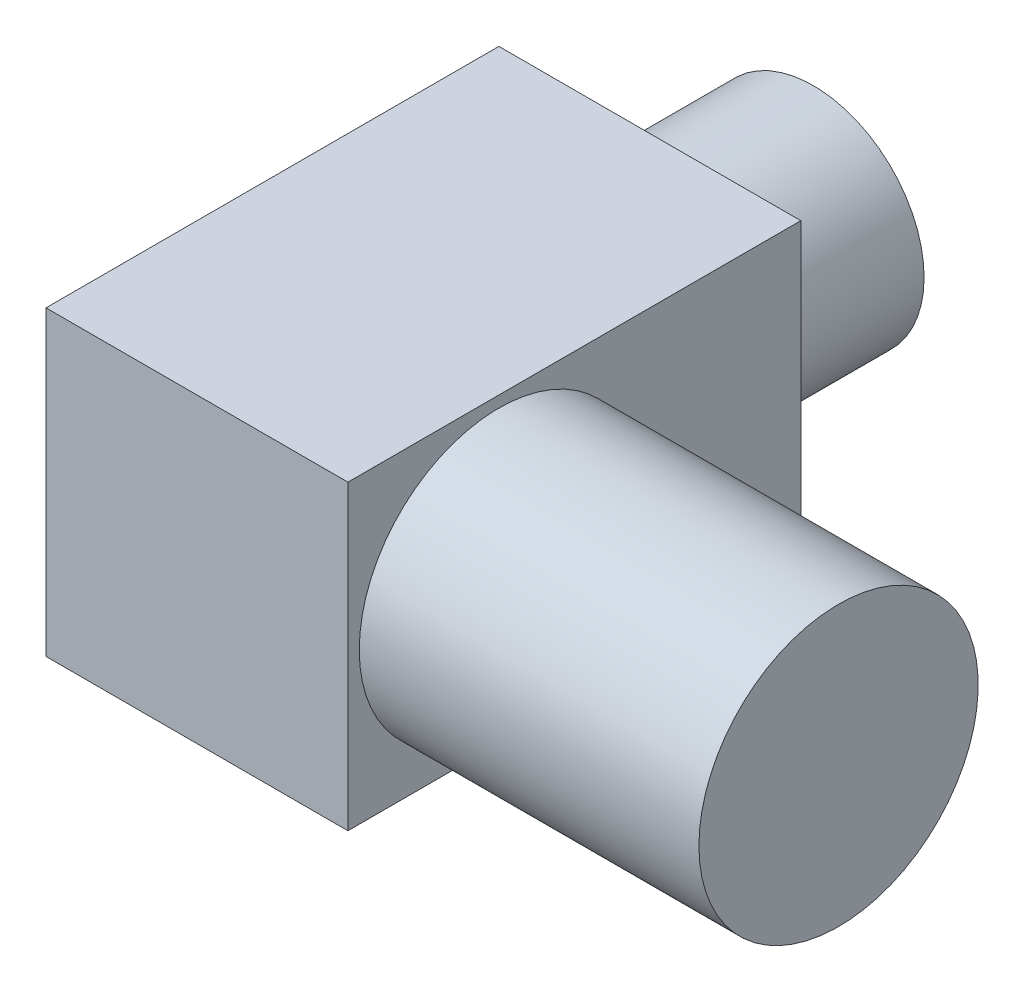
SolidWorks part; units mm, degrees
ref_plane "Front Plane" through (0, 0, 0) normal (0, 0, 1) x (1, 0, 0)
ref_plane "Top Plane" through (0, 0, 0) normal (0, 1, 0) x (1, 0, 0)
ref_plane "Right Plane" through (0, 0, 0) normal (1, 0, 0) x (0, 0, -1)
sketch "Sketch1" plane through (0, 0, 0) normal (0, 0, 1) x (1, 0, 0)
  circle A0 centre (0, 0) radius 4.4
extrude "Rc 1/8 connection, thread core envelope" add sketch "Sketch1" along normal blind 6.5 from offset 6.5
sketch "Sketch2" plane through (0, 0, 0) normal (0, 0, 1) x (1, 0, 0)
  line L0 (-6, -6) -> (6, -6)
  line L1 (6, -6) -> (6, 6)
  line L2 (6, 6) -> (-6, 6)
  line L3 (-6, 6) -> (-6, -6)
extrude "Elbow body and 12 mm wrench flats" add sketch "Sketch2" along normal blind 18
sketch "Sketch3" plane through (0, 0, 0) normal (1, 0, 0) x (0, 0, -1)
  circle A0 centre (-12, 0) radius 5.55
extrude "Male -4 JIC outlet envelope" add sketch "Sketch3" along normal blind 13.7 from offset 5.8
